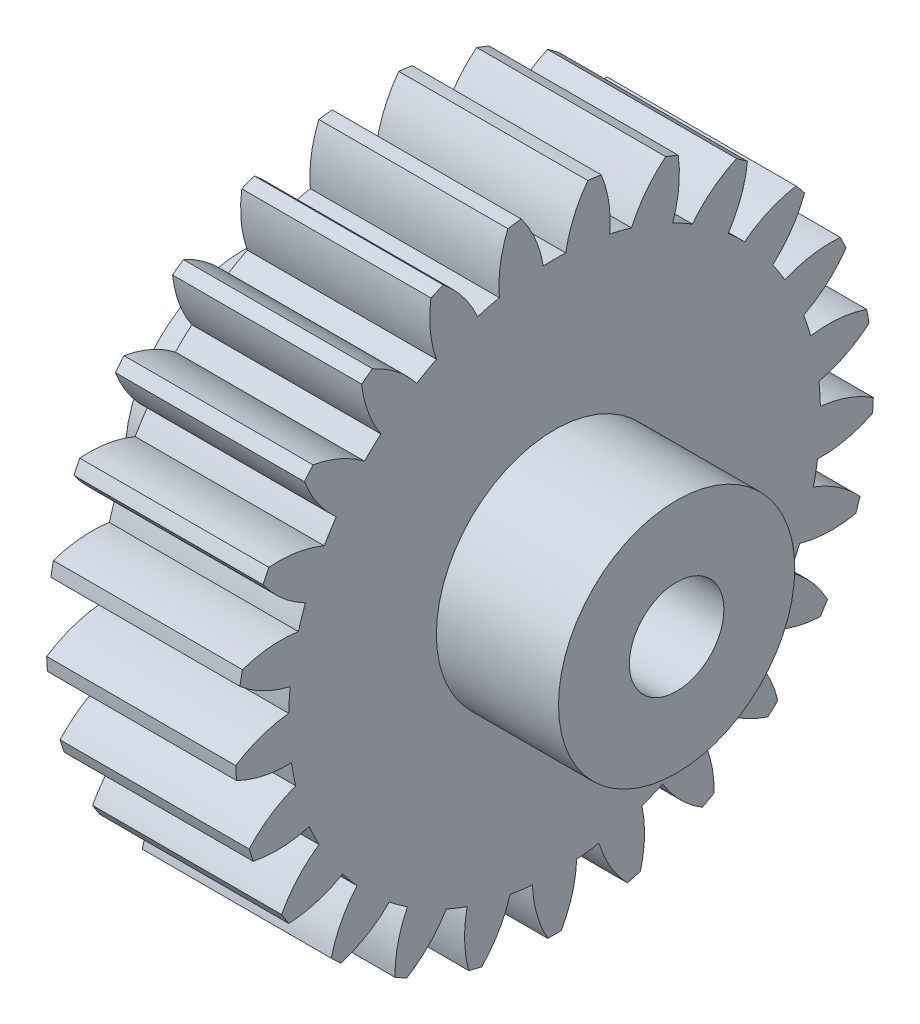
SolidWorks part; units mm, degrees
ref_plane "Plane1" through (0, 0, 0) normal (0, 0, 1) x (1, 0, 0)
ref_plane "Plane2" through (0, 0, 0) normal (0, 1, 0) x (1, 0, 0)
ref_plane "Plane3" through (0, 0, 0) normal (1, 0, 0) x (0, 0, -1)
sketch "HoldingSke" plane through (0, 0, 0) normal (0, 1, 0) x (1, 0, 0)
  line L0 (0, 0) -> (0.6042, -0.2817)
  line L1 (-15, 0) -> (100, 0) construction
  line L2 (0, 0) -> (-2.1039, 2.3779)
  line L3 (0, 0) -> (-11.863, 4.5341)
  line L4 (0, 0) -> (7.8269, 3.6497)
  line L5 (0, 0) -> (-25.7662, -9.61)
  line L6 (0, 0) -> (-9.9476, -6.7116)
  line L7 (-2.1039, 2.3779) -> (3.8155, 29.2333)
  line L8 (-76.2, 54.61) -> (-75.2, 54.61)
  line L9 (-71.009, 38.7566) -> (-53.1078, 45.2721)
  line L10 (-76.2, 71.12) -> (104.1128, 71.12)
  line L11 (0, 0) -> (-12, 0)
  line L12 (-76.2, 101.6) -> (-76.147, 101.6)
  line L13 (24.9733, 27.94) -> (52.9518, 28.4284)
  line L14 (24.9733, 27.94) -> (24.9743, 27.94)
  line L15 (24.9733, 27.94) -> (100.4006, 29.5858)
  line L16 (-63.627, -1.5) -> (-12.827, -1.5)
  circle A0 centre (0, 0) radius 3
  circle A1 centre (0, 0) radius 7.5
  circle A2 centre (0, 0) radius 7.5
  circle A3 centre (0, 0) radius 3
  dimension "MHD" = 15
  dimension "Hub_dia" = 15
  dimension "Bore" = 6
  dimension "MBD" = 6
  dimension "Num_teeth" = 25
  dimension "Pitch" = 0.6667
  dimension "Overall_len" = 27.5
  dimension "Show_teeth" = 25
  dimension "Thickness" = 12
  dimension "OAL" = 27.5001
  dimension "T_dim" = 1
  dimension "Ap" = 20
  dimension "H" = 19.05
  dimension "Pitch_radius" = 180.3128
  dimension "Width" = 12
  dimension "Backlash" = 0.053
  dimension "Addendum_fac" = 1
  dimension "Dedendum_fac" = 1.25
  dimension "Clearance_fac" = 0.25
  dimension "Dedendum_add" = 0.001
  dimension "Module" = 1.5
sketch "BasProSke" plane through (0, 0, 0) normal (0, 1, 0) x (1, 0, 0)
  line L0 (-10, 0) -> (60, 0) construction
  line L1 (0, 0) -> (0, 20.25)
  line L2 (0, 0) -> (12, 0)
  line L3 (12, 0) -> (12, 20.25)
  line L4 (12, 20.25) -> (0, 20.25)
  dimension "Thickness" = 12
  dimension "Diameter" = 40.5
revolve "Base-Revolve" add sketch "BasProSke" angle 360 about L0
sketch "TooCutSke" plane through (0, 0, 0) normal (1, 0, 0) x (0, 0, -1)
  line L1 (0, 0) -> (0, 107) construction
  line L2 (0, 0) -> (-1.27, 18.7069) construction
  line L3 (0, 0) -> (-4.6921, 37.142) construction
  line L4 (-1.27, 18.7069) -> (-2.3461, 18.571) construction
  arc A0 (0.7139, 16.8589) -> (-0.7139, 16.8589) centre (0, 0) ccw
  arc A1 (2.1318, 20.163) -> (-2.1318, 20.163) centre (0, 0) ccw
  circle A2 centre (0, 0) radius 18.75 construction
  circle A3 centre (0, 0) radius 17.6192 construction
  arc A4 (-0.7139, 16.8589) -> (-2.1318, 20.163) centre (-8.1141, 15.6396) ccw
  arc A5 (2.1318, 20.163) -> (0.7139, 16.8589) centre (8.1141, 15.6396) ccw
  dimension "Root_dia" = 33.748
  dimension "Overcut_dia" = 40.5508
  dimension "Pitch_dia" = 37.5
  dimension "Base_dia" = 35.2385
  dimension "Flank_rad" = 7.5
  dimension "Half_ang" = 7.2
  dimension "Half_CT" = 1.0846
extrude "ToothCut" cut sketch "TooCutSke" along normal through all
fillet "Breaks" [suppressed] radius 0.03
fillet "RootFillets" [suppressed] radius 0.376
pattern_circular "TeethCuts" count 25 every 14.4 about axis through (-10, 0, 0) along (1, 0, 0) of "ToothCut", "RootFillets", "Breaks"
sketch "HubNeaOneSke" plane through (0, 0, 0) normal (-1, 0, 0) x (0, 0, 1)
  circle A0 centre (0, 0) radius 7.5
  dimension "Diameter" = 15
extrude "HubNearOne" [suppressed] add sketch "HubNeaOneSke" along normal blind 15.5001
sketch "HubNeaBotSke" plane through (0, 0, 0) normal (-1, 0, 0) x (0, 0, 1)
  circle A0 centre (0, 0) radius 7.5
  dimension "Diameter" = 15
extrude "HubNearBoth" add sketch "HubNeaBotSke" along normal blind 7.75
ref_plane "FarPln" through (12, 0, 0) normal (1, 0, 0) x (0, 0, -1)
sketch "HubFarSke" plane through (12, 0, 0) normal (1, 0, 0) x (0, 0, -1)
  circle A0 centre (0, 0) radius 7.5
  dimension "Diameter" = 15
extrude "HubFar" add sketch "HubFarSke" along normal blind 7.75
sketch "BorSke" plane through (0, 0, 0) normal (1, 0, 0) x (0, 0, -1)
  circle A0 centre (0, 0) radius 3
  dimension "Diameter" = 6
extrude "Bore" cut sketch "BorSke" along normal mid plane 55.0001
sketch "KeySke" plane through (0, 0, 0) normal (1, 0, 0) x (0, 0, -1)
  line L0 (-1, 0) -> (-1, 4)
  line L1 (-1, 4) -> (1, 4)
  line L2 (1, 4) -> (1, 0)
  line L3 (0, 0) -> (0, 34) construction
  line L4 (-1, 0) -> (1, 0)
  dimension "Offset" = 4
  dimension "Width" = 2
extrude "Keyway" [suppressed] cut sketch "KeySke" along normal mid plane 55.0001
pattern_circular "Keyway2" [suppressed] count 2 every 90 about axis through (-10, 0, 0) along (1, 0, 0)
sketch "Sketch1" plane through (0, 0, 0) normal (-1, 0, 0) x (0, 0, 1)
  circle A0 centre (-8.7, -7.5206) radius 2
  point P3 (0, 0)
extrude "Cut-Extrude1" cut sketch "Sketch1" against normal blind 15
equation "' \"Module@HoldingSke\" = 6.35"
equation "' \"Num_teeth@HoldingSke\" = 12"
equation "' \"Ap@HoldingSke\" =  20"
equation "' \"Ap@HoldingSke\" = 20"
equation "' \"Width@HoldingSke\" = 0.5 * 25.4"
equation "' \"Hub_dia@HoldingSke\"= 1 * 25.4"
equation "' \"Hub_dia@HoldingSke\" = 1 * 25.4"
equation "' \"Overall_len@HoldingSke\" = 1.0 * 25.4"
equation "' \"Bore@HoldingSke\" = 0.75 * 25.4"
equation "' \"T_dim@HoldingSke\" = 0.1 * 25.4"
equation "' \"Width@KeySke\" = 0.25 * 25.4"
equation "' \"Show_teeth@HoldingSke\" = 13"
equation "' \"Backlash@HoldingSke\" = 0.009 * 25.4"
equation "' \"Addendum_fac@HoldingSke\" = 1.0"
equation "' \"Dedendum_fac@HoldingSke\" = 1.25"
equation "' \"Dedendum_add@HoldingSke\" = 0.00005 * 25.4"
equation "' \"Clearance_fac@HoldingSke\" = 0.25"
equation "\"Pitch@HoldingSke\" = 1 / \"Module@HoldingSke\""
equation "\"Overcut_dia@TooCutSke\" = (\"Num_teeth@HoldingSke\" + 2 * \"Addendum_fac@HoldingSke\") / \"Pitch@HoldingSke\" + 0.002 * 25.4"
equation "\"Pitch_dia@TooCutSke\" = \"Num_teeth@HoldingSke\" / \"Pitch@HoldingSke\""
equation "\"Base_dia@TooCutSke\" = \"Num_teeth@HoldingSke\" / \"Pitch@HoldingSke\" * cos((\"Ap@HoldingSke\"  * 3.14159265 / 180))"
equation "\"Root_dia@TooCutSke\" = (\"Num_teeth@HoldingSke\" + 2) / \"Pitch@HoldingSke\" - 2 * (\"Addendum_fac@HoldingSke\" + \"Dedendum_fac@HoldingSke\") / \"Pitch@HoldingSke\" - \"Dedendum_add@HoldingSke\" * 2"
equation "\"Half_ang@TooCutSke\" = 180 / \"Num_teeth@HoldingSke\""
equation "\"Half_CT@TooCutSke\" = \"Num_teeth@HoldingSke\" / \"Pitch@HoldingSke\" * sin((3.14159265 / 2 / \"Num_teeth@HoldingSke\")) / 2 - 7 * \"Backlash@HoldingSke\" / 4"
equation "\"Flank_rad@TooCutSke\" = \"Num_teeth@HoldingSke\" / \"Pitch@HoldingSke\" / 5"
equation "\"Radius@RootFillets\" = \"Clearance_fac@HoldingSke\" / \"Pitch@HoldingSke\" + \"Dedendum_add@HoldingSke\""
equation "\"Break_rad@Breaks\" = 0.02 / \"Pitch@HoldingSke\""
equation "\"Thickness@HoldingSke\" = \"Width@HoldingSke\""
equation "\"OAL@HoldingSke\" = \"Thickness@HoldingSke\""
equation "\"MHD@HoldingSke\" = (\"Num_teeth@HoldingSke\" + 2) / \"Pitch@HoldingSke\" - 2 * (\"Addendum_fac@HoldingSke\" + \"Dedendum_fac@HoldingSke\")  / \"Pitch@HoldingSke\" - \"Dedendum_add@HoldingSke\" * 2"
equation "\"MBD@HoldingSke\" = (\"Num_teeth@HoldingSke\" + 2) / \"Pitch@HoldingSke\" - 2 * (\"Addendum_fac@HoldingSke\" + \"Dedendum_fac@HoldingSke\")  / \"Pitch@HoldingSke\" - \"Dedendum_add@HoldingSke\" * 2 - 0.002 * 25.4"
equation "\"MHD@HoldingSke\" = ((sgn( \"MHD@HoldingSke\" - \"Hub_dia@HoldingSke\" )-1)*( \"MHD@HoldingSke\" - \"Hub_dia@HoldingSke\" ))/-2+ \"Hub_dia@HoldingSke\""
equation "\"MBD@HoldingSke\" = ((sgn( \"MBD@HoldingSke\" - \"Bore@HoldingSke\" )-1)*( \"MBD@HoldingSke\" - \"Bore@HoldingSke\" ))/-2+ \"Bore@HoldingSke\""
equation "\"OAL@HoldingSke\" = ((sgn( \"OAL@HoldingSke\" - \"Overall_len@HoldingSke\" )+1)*( \"OAL@HoldingSke\" - \"Overall_len@HoldingSke\" ))/2 + \"Overall_len@HoldingSke\" + 0.000002 * 25.4"
equation "\"Num_teeth@TeethCuts\" = int( \"Show_teeth@HoldingSke\" ) + 1"
equation "\"Num_teeth@TeethCuts\" = ((sgn( \"Num_teeth@TeethCuts\" - \"Num_teeth@HoldingSke\" )-1)*( \"Num_teeth@TeethCuts\" - \"Num_teeth@HoldingSke\" ))/-2+ \"Num_teeth@HoldingSke\""
equation "\"Num_teeth@TeethCuts\" = ((sgn( \"Num_teeth@TeethCuts\" - 2.0)+1)*( \"Num_teeth@TeethCuts\" - 2.0))/2 +2.0"
equation "\"Angle@TeethCuts\" = 360.0 / \"Num_teeth@HoldingSke\""
equation "\"Diameter@BasProSke\" = (\"Num_teeth@HoldingSke\" + 2 * \"Addendum_fac@HoldingSke\") / \"Pitch@HoldingSke\""
equation "\"Thickness@BasProSke\"  = \"Thickness@HoldingSke\""
equation "' \"Fillet_rad@BasProSke\" =  \"Thickness@HoldingSke\" * 0.05"
equation "' \"Fillet_rad@BasProSke\" = \"Thickness@HoldingSke\" * 0.05"
equation "\"MHD@HoldingSke\" = ((sgn( \"MHD@HoldingSke\" - \"Root_dia@TooCutSke\" )-1)*( \"MHD@HoldingSke\" - \"Root_dia@TooCutSke\" ))/-2+ \"Root_dia@TooCutSke\""
equation "\"Diameter@HubNeaOneSke\" = \"MHD@HoldingSke\""
equation "\"Length@HubNearOne\" = \"OAL@HoldingSke\" - \"Thickness@BasProSke\""
equation "\"Diameter@HubNeaBotSke\" = \"MHD@HoldingSke\""
equation "\"Length@HubNearBoth\" = ( \"OAL@HoldingSke\" - \"Thickness@BasProSke\" ) / 2.0"
equation "\"Thickness@FarPln\" = \"Thickness@BasProSke\""
equation "\"Diameter@HubFarSke\" = \"MHD@HoldingSke\""
equation "\"Length@HubFar\" = ( \"OAL@HoldingSke\" - \"Thickness@BasProSke\" ) / 2.0"
equation "\"Diameter@BorSke\" = \"MBD@HoldingSke\""
equation "\"D1@Bore\" = \"OAL@HoldingSke\" * 2.0"
equation "\"D1@Keyway\" = \"OAL@HoldingSke\" * 2.0"
equation "\"Offset@KeySke\" = \"T_dim@HoldingSke\" + \"MBD@HoldingSke\" / 2.0"
